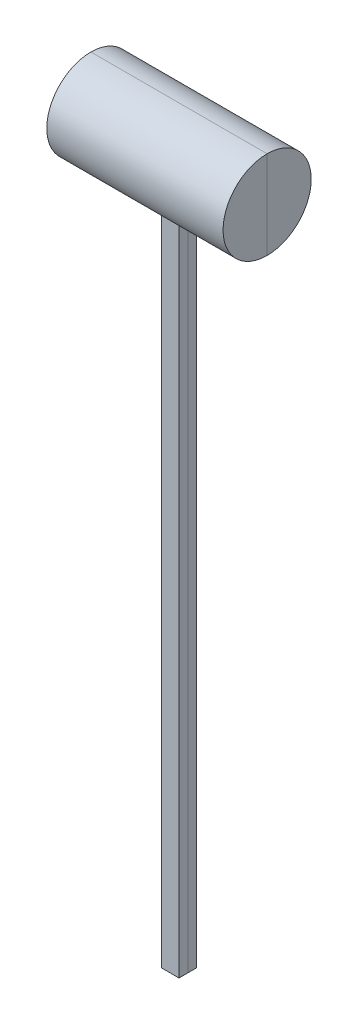
SolidWorks part; units mm, degrees
ref_plane "Front Plane" through (0, 0, 0) normal (0, 0, 1) x (1, 0, 0)
ref_plane "Top Plane" through (0, 0, 0) normal (0, 1, 0) x (1, 0, 0)
ref_plane "Right Plane" through (0, 0, 0) normal (1, 0, 0) x (0, 0, -1)
sketch "Sketch1" plane through (0, 0, 0) normal (1, 0, 0) x (0, 0, -1)
  circle A0 centre (0, 0) radius 5
  dimension "D1" = 10
extrude "Boss-Extrude1" add sketch "Sketch1" along normal mid plane 20
sketch "Sketch2" plane through (0, 0, 0) normal (0, 0, 1) x (1, 0, 0)
  line L1 (-1, 0) -> (1, 0)
  line L2 (-1, 0) -> (-1, -80)
  line L3 (-1, -80) -> (1, -80)
  line L4 (1, 0) -> (1, -80)
  point P4 (0, 0)
  point P5 (0, 0)
  dimension "D1" = 2
  dimension "D2" = 80
extrude "Boss-Extrude2" add sketch "Sketch2" along normal mid plane 2
split "Split1" trim tools "Front Plane" bodies to split 102 resulting bodies 103 104
